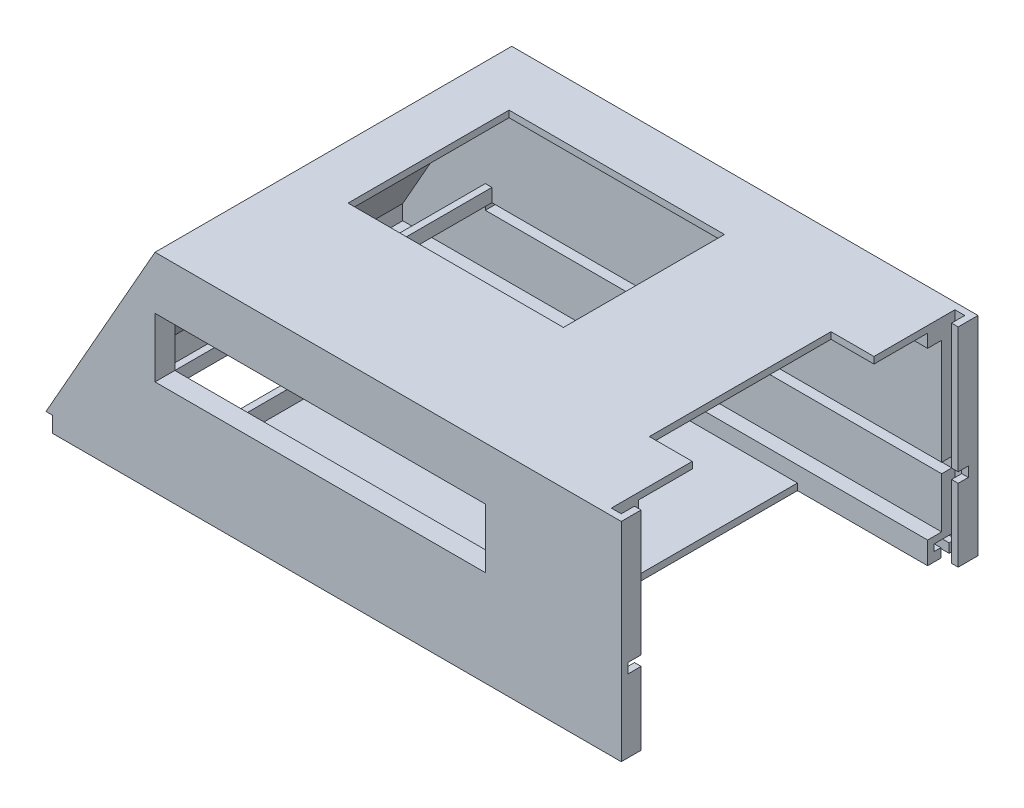
SolidWorks part; units mm, degrees
ref_plane "정면" through (0, 0, 0) normal (0, 0, 1) x (1, 0, 0)
ref_plane "윗면" through (0, 0, 0) normal (0, 1, 0) x (1, 0, 0)
ref_plane "우측면" through (0, 0, 0) normal (1, 0, 0) x (0, 0, -1)
sketch "스케치1" plane through (0, 0, 0) normal (0, 1, 0) x (1, 0, 0)
  line L1 (-87.075, 54) -> (87.075, 54)
  line L2 (-87.075, 54) -> (-87.075, -54)
  line L3 (-87.075, -54) -> (87.075, -54)
  line L4 (87.075, 54) -> (87.075, -54)
  line L5 (-87.075, 54) -> (87.075, -54) construction
  line L6 (-87.075, -54) -> (87.075, 54) construction
  point P0 (0, 0)
  dimension "D1" = 174.15
  dimension "D2" = 108
extrude "보스-돌출1" add sketch "스케치1" along normal blind 63
sketch "스케치4" plane through (87.075, 0, 0) normal (1, 0, 0) x (0, 0, -1)
  line L0 (-50, 0) -> (-50, 3)
  line L1 (-54, 0) -> (54, 0) construction
  line L2 (-50, 3) -> (-52, 3)
  line L3 (-52, 3) -> (-52, 4.5)
  line L4 (-52, 4.5) -> (-46, 4.5)
  line L5 (-46, 4.5) -> (-46, 3)
  line L6 (-46, 3) -> (-48, 3)
  line L7 (-48, 3) -> (-48, 0)
  line L8 (-48, 0) -> (-50, 0)
  line L10 (-54, 63) -> (-54, 0) construction
  line L11 (-50.25, 0) -> (-50.25, 2.75)
  line L12 (-50.25, 2.75) -> (-52.25, 2.75)
  line L13 (-52.25, 2.75) -> (-52.25, 4.75)
  line L14 (-52.25, 4.75) -> (-45.75, 4.75)
  line L15 (-45.75, 4.75) -> (-45.75, 2.75)
  line L16 (-45.75, 2.75) -> (-47.75, 2.75)
  line L17 (-47.75, 2.75) -> (-47.75, 0)
  line L18 (-50, 0) -> (-50.25, 0)
  line L19 (-48, 0) -> (-47.75, 0)
  dimension "D1" = 3
  dimension "D2" = 2
  dimension "D3" = 2
  dimension "D4" = 6
  dimension "D5" = 2
  dimension "D6" = 1.5
  dimension "D7" = 1.5
  dimension "D8" = 0.25
sketch "스케치5" plane through (-87.075, 0, 0) normal (-1, 0, 0) x (0, 0, 1)
  line L0 (50, 0) -> (50, 3) construction
  line L1 (50, 3) -> (52, 3) construction
  line L2 (52, 3) -> (52, 4.5) construction
  line L3 (52, 4.5) -> (46, 4.5) construction
  line L4 (46, 4.5) -> (46, 3) construction
  line L5 (46, 3) -> (48, 3) construction
  line L6 (48, 3) -> (48, 0) construction
  line L7 (48, 0) -> (50, 0) construction
  line L8 (50, 0) -> (50.25, 0) construction
  line L9 (50.25, 0) -> (50.25, 2.75) construction
  line L10 (50.25, 2.75) -> (52.25, 2.75) construction
  line L11 (52.25, 2.75) -> (52.25, 4.75) construction
  line L12 (52.25, 4.75) -> (45.75, 4.75) construction
  line L13 (45.75, 4.75) -> (45.75, 2.75) construction
  line L14 (45.75, 2.75) -> (47.75, 2.75) construction
  line L15 (47.75, 2.75) -> (47.75, 0) construction
  line L16 (48, 0) -> (47.75, 0) construction
  line L17 (50, 0) -> (50, 3)
  line L18 (50, 3) -> (52, 3)
  line L19 (52, 3) -> (52, 4.5)
  line L20 (52, 4.5) -> (46, 4.5)
  line L21 (46, 4.5) -> (46, 3)
  line L22 (46, 3) -> (48, 3)
  line L23 (48, 3) -> (48, 0)
  line L24 (48, 0) -> (50, 0)
  line L25 (50, 0) -> (50.25, 0)
  line L26 (50.25, 0) -> (50.25, 2.75)
  line L27 (50.25, 2.75) -> (52.25, 2.75)
  line L28 (52.25, 2.75) -> (52.25, 4.75)
  line L29 (52.25, 4.75) -> (45.75, 4.75)
  line L30 (45.75, 4.75) -> (45.75, 2.75)
  line L31 (45.75, 2.75) -> (47.75, 2.75)
  line L32 (47.75, 2.75) -> (47.75, 0)
  line L33 (48, 0) -> (47.75, 0)
  line L34 (0, 0) -> (0, 63) construction
  line L35 (-54, 63) -> (54, 63) construction
  line L36 (-48, 0) -> (-47.75, 0)
  line L37 (-47.75, 2.75) -> (-47.75, 0)
  line L38 (-45.75, 2.75) -> (-47.75, 2.75)
  line L39 (-45.75, 4.75) -> (-45.75, 2.75)
  line L40 (-52.25, 4.75) -> (-45.75, 4.75)
  line L41 (-52.25, 2.75) -> (-52.25, 4.75)
  line L42 (-50.25, 2.75) -> (-52.25, 2.75)
  line L43 (-50.25, 0) -> (-50.25, 2.75)
  line L44 (-50, 0) -> (-50.25, 0)
  line L45 (-48, 0) -> (-50, 0)
  line L46 (-48, 3) -> (-48, 0)
  line L47 (-46, 3) -> (-48, 3)
  line L48 (-46, 4.5) -> (-46, 3)
  line L49 (-52, 4.5) -> (-46, 4.5)
  line L50 (-52, 3) -> (-52, 4.5)
  line L51 (-50, 3) -> (-52, 3)
  line L52 (-50, 0) -> (-50, 3)
  line M2 (-54, 0) -> (54, 0)
extrude "컷-돌출2" cut sketch "스케치5" against normal up to surface (174.15 mm away) contours L52 L51 L50 L49 L48 L47 L46 L37 L38 L39 L40 L41 L42 L43 M2 | L52 L46 L47 L48 L49 L50 L51 M2 | L31 L32 L23 L22 L21 L20 L19 L18 L17 L26 L27 L28 L29 L30 M2 | L22 L23 L17 L18 L19 L20 L21 M2 up to face at (87.075, 31.5, 0)
sketch "스케치6" plane through (0, 0, 0) normal (0, -1, 0) x (1, 0, 0)
  line L0 (87.075, -54) -> (-87.075, -54) construction
  line L1 (-87.075, 54) -> (-85.075, 54)
  line L2 (-87.075, 54) -> (-87.075, -54)
  line L3 (-87.075, -54) -> (-85.075, -54)
  line L4 (-85.075, 54) -> (-85.075, -54)
  dimension "D1" = 2
extrude "컷-돌출3" cut sketch "스케치6" against normal up to surface (4.75 mm away) up to face at (0, 4.75, 49)
sketch "스케치7" plane through (87.075, 0, 0) normal (1, 0, 0) x (0, 0, -1)
  line L0 (-54, 63) -> (-54, 0) construction
  line L1 (-48, 57) -> (48, 57)
  line L2 (-48, 57) -> (-48, 6.75)
  line L3 (-48, 6.75) -> (48, 6.75)
  line L4 (48, 57) -> (48, 6.75)
  line L5 (54, 63) -> (54, 0) construction
  line L6 (45.75, 4.75) -> (52.25, 4.75) construction
  line L7 (-54, 63) -> (54, 63) construction
  dimension "D1" = 6
  dimension "D2" = 6
  dimension "D3" = 2
  dimension "D4" = 6
extrude "컷-돌출5" cut sketch "스케치7" against normal blind 168.15
sketch "스케치8" plane through (87.075, 0, 0) normal (1, 0, 0) x (0, 0, -1)
  line L0 (-48, 6.75) -> (48, 6.75) construction
  line L1 (-43.75, 6.75) -> (43.75, 6.75)
  line L2 (-43.75, 6.75) -> (-43.75, 2)
  line L3 (-43.75, 2) -> (43.75, 2)
  line L4 (43.75, 6.75) -> (43.75, 2)
  line L5 (-45.75, 2.75) -> (-45.75, 4.75) construction
  line L6 (-47.75, 0) -> (47.75, 0) construction
  line L7 (45.75, 2.75) -> (45.75, 4.75) construction
  dimension "D1" = 2
  dimension "D2" = 2
  dimension "D3" = 2
extrude "컷-돌출6" cut sketch "스케치8" against normal blind 168.15
sketch "스케치10" plane through (0, 2, 0) normal (0, 1, 0) x (1, 0, 0)
  line L4 (87.075, -43.75) -> (87.075, 43.75)
  line L5 (87.075, 43.75) -> (-81.075, 43.75)
  line L6 (-81.075, 43.75) -> (-81.075, -43.75)
  line L7 (-81.075, -43.75) -> (87.075, -43.75)
  line L8 (87.075, -43.75) -> (87.075, 43.75)
  line L9 (87.075, 43.75) -> (-81.075, 43.75)
  line L10 (-81.075, 43.75) -> (-81.075, -43.75)
  line L11 (-81.075, -43.75) -> (87.075, -43.75)
  dimension "D1" = 0
extrude "컷-돌출8" cut sketch "스케치10" along normal blind 59
ref_plane "평면1" through (0, 24, 0) normal (0, -1, 0) x (-1, 0, 0)
sketch "스케치12" plane through (0, 24, 0) normal (0, -1, 0) x (-1, 0, 0)
  line L1 (-87.075, 48) -> (81.075, 48)
  line L2 (-87.075, 48) -> (-87.075, -48)
  line L3 (-87.075, -48) -> (81.075, -48)
  line L4 (81.075, 48) -> (81.075, -48)
extrude "보스-돌출2" add sketch "스케치12" along normal blind 2
sketch "스케치15" plane through (0, 2, 0) normal (0, 1, 0) x (1, 0, 0)
  line L0 (-81.075, -43.75) -> (87.075, -43.75) construction
  line L1 (-81.075, 43.75) -> (-56.075, 43.75)
  line L2 (-81.075, 43.75) -> (-81.075, -26.25)
  line L3 (-81.075, -26.25) -> (-56.075, -26.25)
  line L4 (-56.075, 43.75) -> (-56.075, -26.25)
  line L5 (-36.7332, -43.75) -> (18.2668, -43.75)
  line L6 (-36.7332, -43.75) -> (-36.7332, -23.75)
  line L7 (-36.7332, -23.75) -> (18.2668, -23.75)
  line L8 (18.2668, -43.75) -> (18.2668, -23.75)
  line L9 (-81.075, 43.75) -> (87.075, 43.75) construction
  line L10 (42.6769, 43.75) -> (87.075, 43.75)
  line L11 (42.6769, 43.75) -> (42.6769, -43.75)
  line L12 (42.6769, -43.75) -> (87.075, -43.75)
  line L13 (87.075, 43.75) -> (87.075, -43.75)
  dimension "D1" = 25
  dimension "D2" = 70
  dimension "D3" = 20
  dimension "D4" = 55
extrude "컷-돌출9" cut sketch "스케치15" against normal blind 2
sketch "스케치16" plane through (0, 24, 0) normal (0, 1, 0) x (1, 0, 0)
  line L0 (87.075, -48) -> (-81.075, -48) construction
  line L1 (-81.075, 48) -> (-56.075, 48)
  line L2 (-81.075, 48) -> (-81.075, -48)
  line L3 (-81.075, -48) -> (-56.075, -48)
  line L4 (-56.075, 48) -> (-56.075, -48)
  line L5 (-81.075, 48) -> (87.075, 48) construction
  line L6 (54.7915, 48) -> (87.075, 48)
  line L7 (54.7915, 48) -> (54.7915, -48)
  line L8 (54.7915, -48) -> (87.075, -48)
  line L9 (87.075, 48) -> (87.075, -48)
  dimension "D1" = 25
extrude "컷-돌출10" cut sketch "스케치16" against normal blind 2
sketch "스케치17" plane through (0, 24, 0) normal (0, 1, 0) x (1, 0, 0)
  line L0 (54.7915, -48) -> (-56.075, -48) construction
  line L1 (-56.075, 48) -> (-54.075, 48)
  line L2 (-56.075, 48) -> (-56.075, -48)
  line L3 (-56.075, -48) -> (-54.075, -48)
  line L4 (-54.075, 48) -> (-54.075, -48)
  dimension "D1" = 2
extrude "보스-돌출3" add sketch "스케치17" along normal blind 5
sketch "스케치18" plane through (0, 2, 0) normal (0, 1, 0) x (1, 0, 0)
  line L0 (-81.075, -43.75) -> (87.075, -43.75) construction
  line L1 (-56.075, 43.75) -> (-54.075, 43.75)
  line L2 (-56.075, 43.75) -> (-56.075, -43.75)
  line L3 (-56.075, -43.75) -> (-54.075, -43.75)
  line L4 (-54.075, 43.75) -> (-54.075, -43.75)
  dimension "D1" = 2
extrude "보스-돌출4" add sketch "스케치18" along normal blind 5
sketch "스케치19" plane through (0, 0, 48) normal (0, 0, -1) x (-1, 0, 0)
  line L0 (54.075, 29) -> (54.075, 24) construction
  line L1 (54.075, 29) -> (-45.925, 29)
  line L2 (54.075, 29) -> (54.075, 47)
  line L3 (54.075, 47) -> (-45.925, 47)
  line L4 (-45.925, 29) -> (-45.925, 47)
  line L5 (-54.7915, 24) -> (54.075, 24) construction
  dimension "D1" = 5
  dimension "D2" = 100
  dimension "D3" = 18
extrude "컷-돌출11" cut sketch "스케치19" against normal blind 6
sketch "스케치20" plane through (0, 0, 54) normal (0, 0, 1) x (1, 0, 0)
  line L0 (-87.075, 4.75) -> (-54.075, 63)
  line L1 (-87.075, 63) -> (87.075, 63) construction
  line L2 (-54.075, 63) -> (-87.075, 63)
  line L3 (-87.075, 63) -> (-87.075, 4.75)
extrude "컷-돌출12" cut sketch "스케치20" against normal up to surface (108 mm away) up to face at (-28.3583, 22.5833, -54)
sketch "스케치21" plane through (0, 0, 54) normal (0, 0, 1) x (1, 0, 0)
  line L0 (-87.075, 4.75) -> (-84.7763, 4.75)
  line L1 (-87.075, 4.75) -> (-54.075, 63)
  line L2 (-84.7763, 4.75) -> (-51.7763, 63)
  line L3 (-54.075, 63) -> (-51.7763, 63)
  line L4 (-54.075, 63) -> (87.075, 63) construction
  dimension "D1" = 2
extrude "보스-돌출5" add sketch "스케치21" against normal up to surface (108 mm away) up to face at (-22.8583, 22.5833, -54)
sketch "스케치23" plane through (0, 63, 0) normal (0, 1, 0) x (1, 0, 0)
  line L5 (-37.7431, 36.8539) -> (27.4625, 36.8539)
  line L6 (-37.7431, 36.8539) -> (-37.7431, -11.8908)
  line L7 (-37.7431, -11.8908) -> (27.4625, -11.8908)
  line L8 (27.4625, 36.8539) -> (27.4625, -11.8908)
extrude "컷-돌출13" cut sketch "스케치23" against normal blind 2
sketch "스케치26" plane through (0, 63, 0) normal (0, 1, 0) x (1, 0, 0)
  line L0 (87.075, 54) -> (-54.075, 54) construction
  line L1 (82.075, 52) -> (85.075, 52)
  line L2 (82.075, 52) -> (82.075, -52)
  line L3 (82.075, -52) -> (85.075, -52)
  line L4 (85.075, 52) -> (85.075, 48)
  line L5 (-54.075, -54) -> (87.075, -54) construction
  line L6 (87.075, -54) -> (87.075, 54) construction
  line L7 (85.075, -48) -> (85.075, -52)
  line L8 (87.075, 48) -> (85.075, 48)
  line L9 (87.075, 48) -> (87.075, -48)
  line L10 (87.075, -48) -> (85.075, -48)
  point P6 (83.575, -52)
  dimension "D1" = 3
  dimension "D2" = 2
  dimension "D3" = 2
  dimension "D4" = 2
  dimension "D5" = 6
  dimension "D6" = 6
extrude "컷-돌출14" cut sketch "스케치26" against normal up to surface (63 mm away)
sketch "스케치28" plane through (0, 4.75, 0) normal (0, -1, 0) x (1, 0, 0)
  line L0 (87.075, 52.25) -> (-85.075, 52.25) construction
  line L1 (87.075, 48) -> (85.075, 48)
  line L2 (87.075, 48) -> (87.075, 52.25)
  line L3 (87.075, 52.25) -> (85.075, 52.25)
  line L4 (85.075, 48) -> (85.075, 52.25)
  line L5 (87.075, -52.25) -> (-85.075, -52.25) construction
  line L6 (87.075, -48) -> (85.075, -48)
  line L7 (87.075, -48) -> (87.075, -52.25)
  line L8 (87.075, -52.25) -> (85.075, -52.25)
  line L9 (85.075, -48) -> (85.075, -52.25)
extrude "보스-돌출6" add sketch "스케치28" along normal up to surface (4.75 mm away) up to face at (42.2875, 0, 51.625)
sketch "스케치29" plane through (0, 63, 0) normal (0, 1, 0) x (1, 0, 0)
  line L0 (82.325, 51.5) -> (84.825, 51.5)
  line L1 (82.325, 51.5) -> (82.325, -51.5)
  line L2 (82.325, -51.5) -> (84.825, -51.5)
  line L3 (84.825, 51.5) -> (84.825, -51.5)
  line L4 (84.825, 47.5) -> (86.825, 47.5)
  line L5 (84.825, 47.5) -> (84.825, -47.5)
  line L6 (84.825, -47.5) -> (86.825, -47.5)
  line L7 (86.825, 47.5) -> (86.825, -47.5)
  line L8 (85.075, 52) -> (82.075, 52) construction
  line L9 (82.075, 52) -> (82.075, -52) construction
  dimension "D1" = 2.5
  dimension "D2" = 4
  dimension "D3" = 0.5
  dimension "D4" = 0.25
sketch "스케치31" plane through (0, 63, 0) normal (0, 1, 0) x (1, 0, 0)
  line L1 (69.075, 27.5) -> (82.075, 27.5)
  line L2 (69.075, 27.5) -> (69.075, -27.5)
  line L3 (69.075, -27.5) -> (82.075, -27.5)
  line L4 (82.075, 27.5) -> (82.075, -27.5)
  line L5 (87.075, 54) -> (-54.075, 54) construction
  line L6 (82.075, 52) -> (82.075, -52) construction
  dimension "D1" = 13
  dimension "D2" = 55
  dimension "D3" = 26.5
extrude "컷-돌출15" cut sketch "스케치31" against normal blind 10
sketch "스케치34" plane through (87.075, 0, 0) normal (1, 0, 0) x (0, 0, -1)
  line L0 (-54, 63) -> (-54, 0) construction
  line L1 (-52, 22) -> (51.0709, 22)
  line L2 (-52, 22) -> (-52, 25)
  line L3 (-52, 25) -> (51.0709, 25)
  line L4 (51.0709, 22) -> (51.0709, 25)
  dimension "D1" = 2
  dimension "D2" = 3
extrude "컷-돌출16" cut sketch "스케치34" against normal blind 143.15 contours L3 L4 L1 L2
sketch "스케치36" plane through (87.075, 0, 0) normal (1, 0, 0) x (0, 0, -1)
  line L0 (-52, 23.5) -> (51.0709, 23.5)
  line L1 (-52, 22) -> (-52, 25) construction
  line L2 (51.0709, 22) -> (51.0709, 25) construction
  dimension "D1" = 103.0709
